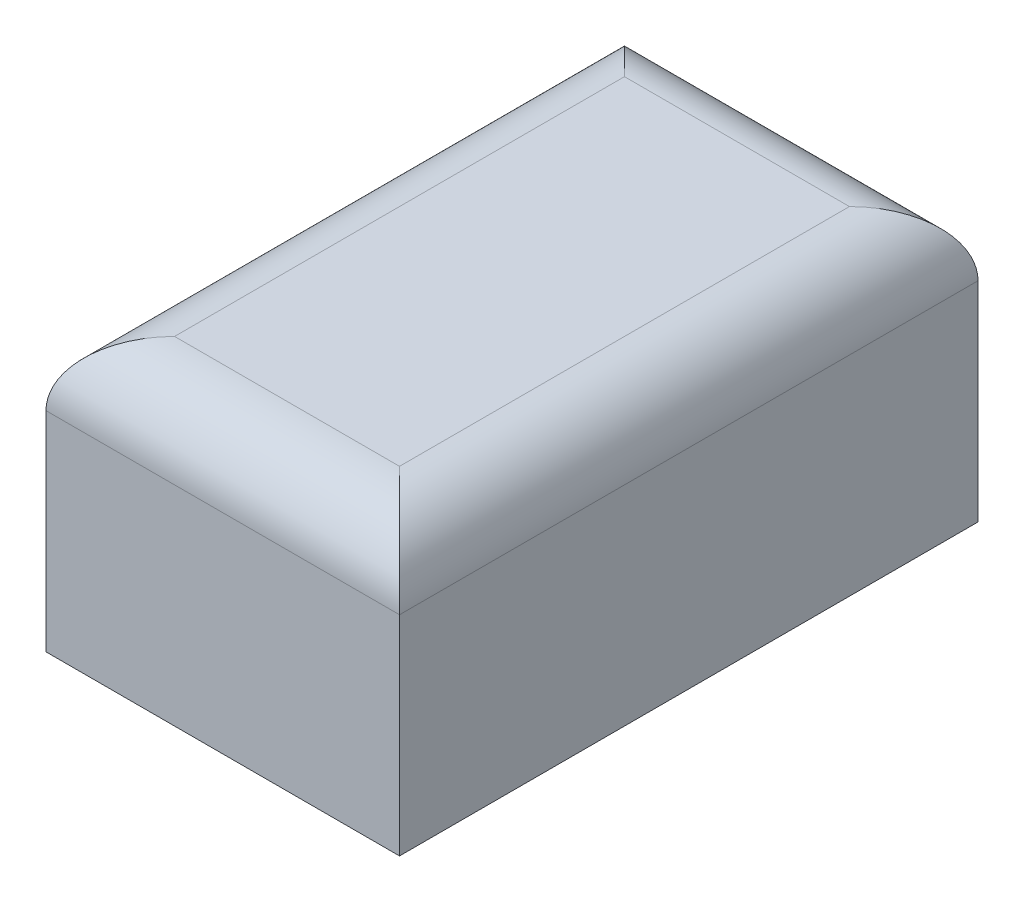
SolidWorks part; units mm, degrees
ref_plane "Front Plane" through (0, 0, 0) normal (0, 0, 1) x (1, 0, 0)
ref_plane "Top Plane" through (0, 0, 0) normal (0, 1, 0) x (1, 0, 0)
ref_plane "Right Plane" through (0, 0, 0) normal (1, 0, 0) x (0, 0, -1)
sketch "Sketch1" plane through (0, 0, 0) normal (0, 1, 0) x (1, 0, 0)
  line L1 (-11, -18) -> (11, -18)
  line L2 (-11, -18) -> (-11, 18)
  line L3 (-11, 18) -> (11, 18)
  line L4 (11, -18) -> (11, 18)
  line L5 (-11, -18) -> (11, 18) construction
  line L6 (-11, 18) -> (11, -18) construction
  point P0 (0, 0)
  dimension "D1" = 22
  dimension "D2" = 36
extrude "Boss-Extrude1" add sketch "Sketch1" along normal blind 17
sketch "Sketch2" plane through (0, 0, 0) normal (0, -1, 0) x (-1, 0, 0)
  line L1 (8, 15) -> (-8, 15)
  line L2 (8, 15) -> (8, -15)
  line L3 (8, -15) -> (-8, -15)
  line L4 (-8, 15) -> (-8, -15)
  line L5 (8, 15) -> (-8, -15) construction
  line L6 (8, -15) -> (-8, 15) construction
  point P0 (0, 0)
  dimension "D1" = 30
  dimension "D2" = 16
extrude "Cut-Extrude1" cut sketch "Sketch2" against normal blind 14
fillet "Fillet1" radius 4 4 edges at (0, 17, -18) (11, 17, 0) (0, 17, 18) (-11, 17, 0)
ref_plane "Plane3" through (0, 21, 0) normal (0, 1, 0) x (1, 0, 0)
sketch "Sketch10" plane through (0, 21, 0) normal (0, 1, 0) x (1, 0, 0)
  circle A0 centre (0, 0) radius 3
  dimension "D1" = 6
